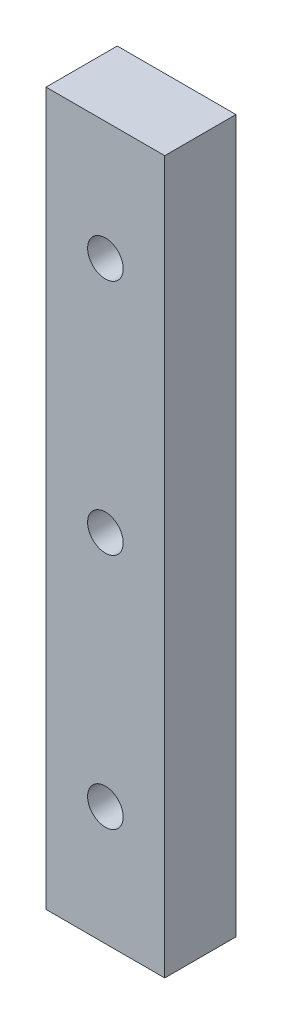
SolidWorks part; units mm, degrees
ref_plane "Plan de face" through (0, 0, 0) normal (0, 0, 1) x (1, 0, 0)
ref_plane "Plan de dessus" through (0, 0, 0) normal (0, 1, 0) x (1, 0, 0)
ref_plane "Plan de droite" through (0, 0, 0) normal (1, 0, 0) x (0, 0, -1)
sketch "Esquisse1" plane through (0, 0, 0) normal (0, 0, 1) x (1, 0, 0)
  line L1 (-5, -30) -> (5, -30)
  line L2 (-5, -30) -> (-5, 30)
  line L3 (-5, 30) -> (5, 30)
  line L4 (5, -30) -> (5, 30)
  line L5 (-5, -30) -> (5, 30) construction
  line L6 (-5, 30) -> (5, -30) construction
  point P0 (0, 0)
  dimension "D1" = 10
  dimension "D2" = 60
extrude "Extrusion1" add sketch "Esquisse1" along normal blind 6
sketch "Esquisse2" plane through (0, 0, 6) normal (0, 0, 1) x (1, 0, 0)
  circle A0 centre (0, -20) radius 1.5
  circle A1 centre (0, 0) radius 1.5
  circle A2 centre (0, 20) radius 1.5
extrude "Enlèv. mat.-Extru.1" cut sketch "Esquisse2" against normal blind 10
